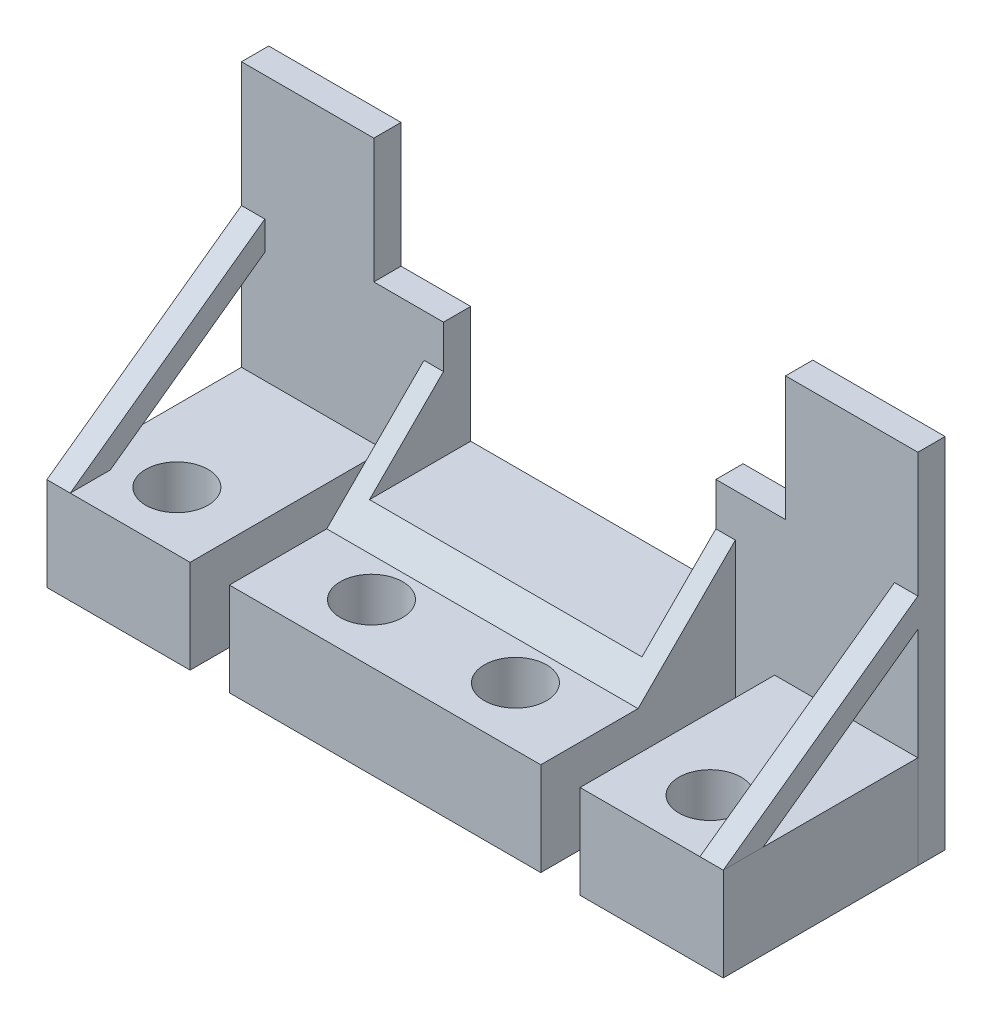
SolidWorks part; units mm, degrees
ref_plane "Front Plane" through (0, 0, 0) normal (0, 0, 1) x (1, 0, 0)
ref_plane "Top Plane" through (0, 0, 0) normal (0, 1, 0) x (1, 0, 0)
ref_plane "Right Plane" through (0, 0, 0) normal (1, 0, 0) x (0, 0, -1)
sketch "Sketch1" plane through (0, 0, 0) normal (0, 1, 0) x (1, 0, 0)
  line L0 (20, 0) -> (20, 25) construction
  line L1 (0, 0) -> (40, 0)
  line L2 (0, 0) -> (0, 25)
  line L3 (0, 25) -> (40, 25)
  line L4 (40, 0) -> (40, 25)
  line L5 (10.75, 7.5) -> (10.75, 0) construction
  line L6 (20, 0) -> (-14.25, 0) construction
  line L15 (0, 7.5) -> (-5.05, 7.5) construction
  line L16 (-14.25, 0) -> (-14.25, 7.5) construction
  line L17 (-23.45, 25) -> (-5.05, 25)
  line L18 (-23.45, 25) -> (-23.45, 0)
  line L19 (-23.45, 0) -> (-5.05, 0)
  line L20 (-5.05, 25) -> (-5.05, 0)
  line L24 (63.45, 0) -> (45.05, 0)
  line L25 (45.05, 25) -> (45.05, 0)
  line L26 (63.45, 25) -> (45.05, 25)
  line L27 (63.45, 25) -> (63.45, 0)
  circle A0 centre (10.75, 7.5) radius 4
  circle A4 centre (-14.25, 7.5) radius 4
  circle A5 centre (54.25, 7.5) radius 4
  circle A6 centre (29.25, 7.5) radius 4
  dimension "D4" = 8
  dimension "D1" = 40
  dimension "D2" = 25
  dimension "D3" = 9.25
  dimension "D5" = 34.25
  dimension "D6" = 5.05
  dimension "D7" = 7.5
extrude "Boss-Extrude1" add sketch "Sketch1" along normal blind 12
ref_plane "Plane1" through (20, 0, 0) normal (-1, 0, 0) x (0, 0, 1)
sketch "Sketch2" plane through (20, 0, 0) normal (-1, 0, 0) x (0, 0, 1)
  line L1 (-25, 0) -> (-28.5, 0)
  line L2 (-25, 0) -> (-25, 30)
  line L3 (-25, 30) -> (-28.5, 30)
  line L4 (-28.5, 0) -> (-28.5, 30)
  dimension "D1" = 3.5
  dimension "D2" = 30
extrude "Boss-Extrude2" add sketch "Sketch2" along normal up to surface and the other way up to surface
sketch "Sketch3" plane through (-23.45, 0, 0) normal (-1, 0, 0) x (0, 0, 1)
  line L0 (0, 12) -> (-25, 30)
  line L1 (-25, 30) -> (-25, 26.3033)
  line L2 (-25, 30) -> (-25, 0) construction
  line L3 (-25, 26.3033) -> (-5.1343, 12)
  line L4 (-25, 12) -> (0, 12) construction
  line L5 (-5.1343, 12) -> (0, 12)
  line L6 (-15.0672, 19.1516) -> (-13.3142, 21.5863) construction
  dimension "D1" = 3
extrude "Boss-Extrude3" add sketch "Sketch3" against normal blind 3
mirror "Mirror1" about plane through (20, 0, 0) normal (-1, 0, 0) of "Boss-Extrude3"
sketch "Sketch4" plane through (0, 0, 0) normal (-1, 0, 0) x (0, 0, 1)
  line L0 (-12.5, 12) -> (-25, 24.5)
  line L1 (-25, 12) -> (0, 12) construction
  line L2 (-25, 24.5) -> (-25, 12)
  line L3 (-25, 12) -> (-12.5, 12)
extrude "Boss-Extrude4" add sketch "Sketch4" against normal up to surface (40 mm away) up to face at (40, 6, -12.5)
sketch "Sketch5" plane through (0, 0, -28.5) normal (0, 0, -1) x (-1, 0, 0)
  line L0 (23.45, 30) -> (-63.45, 30) construction
  line L1 (-2.5, 30) -> (-37.5, 30)
  line L2 (-2.5, 30) -> (-2.5, 15)
  line L3 (-2.5, 15) -> (-37.5, 15)
  line L4 (-37.5, 30) -> (-37.5, 15)
  point P6 (-20, 30)
  point P7 (-20, 30)
  dimension "D1" = 35
  dimension "D2" = 15
extrude "Cut-Extrude1" cut sketch "Sketch5" against normal up to vertex
sketch "Sketch6" plane through (0, 30, 0) normal (0, 1, 0) x (1, 0, 0)
  line L0 (-23.45, 28.5) -> (2.5, 28.5) construction
  line L1 (-23.45, 25) -> (-6.45, 25)
  line L2 (-23.45, 25) -> (-23.45, 28.5)
  line L3 (-23.45, 28.5) -> (-6.45, 28.5)
  line L4 (-6.45, 25) -> (-6.45, 28.5)
  dimension "D1" = 17
extrude "Boss-Extrude5" add sketch "Sketch6" along normal blind 16
mirror "Mirror2" about plane through (20, 0, 0) normal (-1, 0, 0) of "Boss-Extrude5"
equation "\"verticalSlideWidth\"=14.45"
